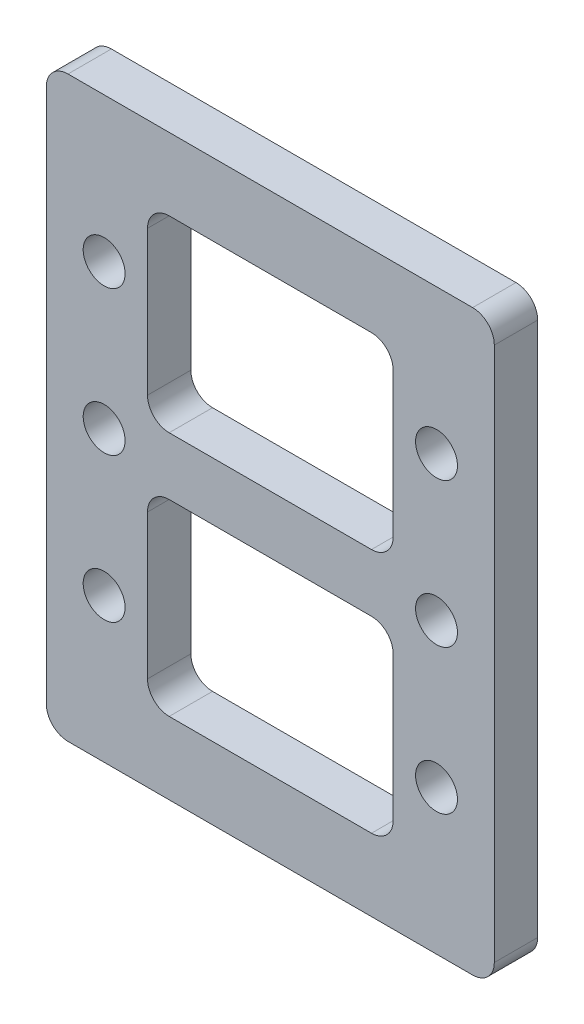
SolidWorks part; units mm, degrees
material "Thornel Mat VMA"
ref_plane "前视基准面" through (0, 0, 0) normal (0, 0, 1) x (1, 0, 0)
ref_plane "上视基准面" through (0, 0, 0) normal (0, 1, 0) x (1, 0, 0)
ref_plane "右视基准面" through (0, 0, 0) normal (1, 0, 0) x (0, 0, -1)
sketch "草图1" plane through (0, 0, 0) normal (0, 0, 1) x (1, 0, 0)
  line L0 (4, 20) -> (27, 20) construction
  line L1 (0, 0) -> (31, 0)
  line L2 (0, 0) -> (0, 40)
  line L3 (0, 40) -> (31, 40)
  line L4 (31, 0) -> (31, 40)
  line L5 (4, 30) -> (27, 30) construction
  line L6 (4, 30) -> (4, 10) construction
  line L7 (4, 10) -> (27, 10) construction
  line L8 (27, 30) -> (27, 10) construction
  circle A0 centre (4, 30) radius 1.45
  circle A1 centre (4, 20) radius 1.45
  circle A2 centre (4, 10) radius 1.45
  circle A3 centre (27, 30) radius 1.45
  circle A4 centre (27, 20) radius 1.45
  circle A5 centre (27, 10) radius 1.45
  dimension "D3" = 2.9
  dimension "D4" = 2.9
  dimension "D5" = 2.9
  dimension "D6" = 2.9
  dimension "D7" = 2.9
  dimension "D8" = 2.9
  dimension "D1" = 20
  dimension "D2" = 23
  dimension "D9" = 4
  dimension "D10" = 4
  dimension "D11" = 10
  dimension "D12" = 10
extrude "凸台-拉伸1" add sketch "草图1" along normal blind 3
sketch "草图2" plane through (0, 0, 3) normal (0, 0, 1) x (1, 0, 0)
  line L0 (31, 40) -> (0, 40) construction
  line L1 (7, 35) -> (24, 35)
  line L2 (7, 35) -> (7, 22)
  line L3 (7, 22) -> (24, 22)
  line L4 (24, 35) -> (24, 22)
  line L5 (7, 18) -> (24, 18)
  line L6 (7, 18) -> (7, 5)
  line L7 (7, 5) -> (24, 5)
  line L8 (24, 18) -> (24, 5)
  circle A0 centre (4, 30) radius 1.45 construction
  circle A2 centre (4, 10) radius 1.45 construction
  circle A4 centre (4, 20) radius 1.45 construction
  circle A5 centre (27, 30) radius 1.45 construction
  circle A6 centre (27, 10) radius 1.45 construction
  point P8 (23.3206, 17)
  point P9 (22.7052, 5)
  point P25 (14, 18.8078)
  point P26 (7, 13.3205)
  dimension "D4" = 3
  dimension "D7" = 2
  dimension "D8" = 2
  dimension "D1" = 3
  dimension "D2" = 3
  dimension "D3" = 3
  dimension "D9" = 5
extrude "切除-拉伸1" cut sketch "草图2" against normal blind 3
fillet "圆角1" radius 1.5 12 edges at (31, 40, 1.5) (31, 0, 1.5) (0, 0, 1.5) (24, 22, 1.5) (24, 35, 1.5) (7, 35, 1.5) (7, 22, 1.5) (24, 5, 1.5) (24, 18, 1.5) (7, 18, 1.5) (7, 5, 1.5) (0, 40, 1.5)
